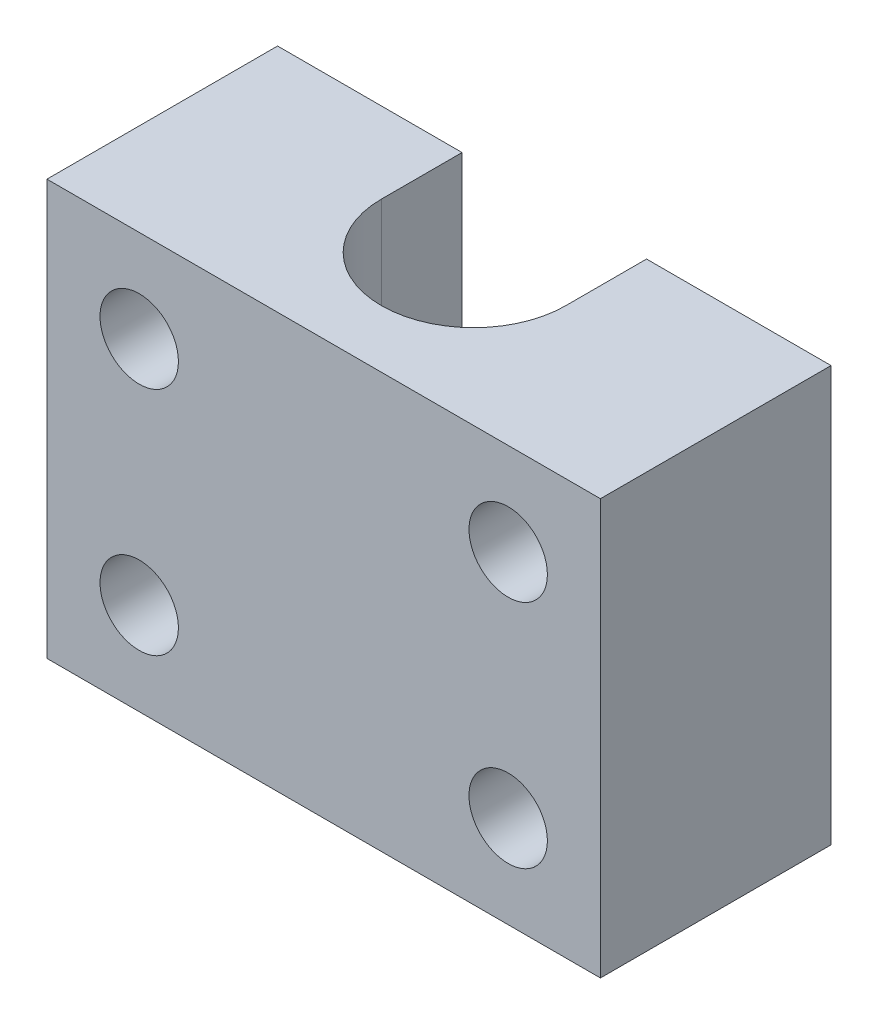
SolidWorks part; units mm, degrees
ref_plane "Front Plane" through (0, 0, 0) normal (0, 0, 1) x (1, 0, 0)
ref_plane "Top Plane" through (0, 0, 0) normal (0, 1, 0) x (1, 0, 0)
ref_plane "Right Plane" through (0, 0, 0) normal (1, 0, 0) x (0, 0, -1)
ref_plane "Plane1" through (0, 0, 6.5) normal (0, 0, 1) x (1, 0, 0)
sketch "Sketch1" plane through (0, 0, 6.5) normal (0, 0, 1) x (1, 0, 0)
  line L0 (12, 9) -> (-12, 9)
  line L1 (-12, 9) -> (-12, -9)
  line L2 (-12, -9) -> (12, -9)
  line L3 (12, -9) -> (12, 9)
extrude "Boss-Extrude1" add sketch "Sketch1" against normal blind 10
sketch "Sketch2" plane through (0, 9, 0) normal (0, 1, 0) x (-1, 0, 0)
  line L0 (-4, -3.5) -> (4, -3.5)
  line L1 (4, -3.5) -> (4, 0)
  line L2 (-4, 0) -> (-4, -3.5)
  arc A0 (4, 0) -> (-4, 0) centre (0, 0) ccw
extrude "Cut-Extrude1" cut sketch "Sketch2" against normal through all
hole_wizard "Hole1" positions "Sketch4" profile "Sketch3" legacy
sketch "Sketch4" plane through (0, 0, 6.5) normal (0, 0, 1) x (1, 0, 0)
  point P0 (8, -5)
sketch "Sketch3" plane through (8, -5, 6.5) normal (1, 0, 0) x (0, -1, 0)
  line L0 (0, 0) -> (0, 10)
  line L1 (0, 10) -> (1.7, 10)
  line L2 (1.7, 10) -> (1.7, 0)
  line L3 (1.7, 0) -> (0, 0)
  line L4 (0, 110) -> (0, -10) construction
  dimension "Diameter" = 3.4
  dimension "Depth" = 10
hole_wizard "Hole2" positions "Sketch6" profile "Sketch5" legacy
sketch "Sketch6" plane through (0, 0, 6.5) normal (0, 0, 1) x (1, 0, 0)
  point P0 (-8, 5)
sketch "Sketch5" plane through (-8, 5, 6.5) normal (1, 0, 0) x (0, -1, 0)
  line L0 (0, 0) -> (0, 10)
  line L1 (0, 10) -> (1.7, 10)
  line L2 (1.7, 10) -> (1.7, 0)
  line L3 (1.7, 0) -> (0, 0)
  line L4 (0, 110) -> (0, -10) construction
  dimension "Diameter" = 3.4
  dimension "Depth" = 10
hole_wizard "Hole3" positions "Sketch8" profile "Sketch7" legacy
sketch "Sketch8" plane through (0, 0, 6.5) normal (0, 0, 1) x (1, 0, 0)
  point P0 (-8, -5)
sketch "Sketch7" plane through (-8, -5, 6.5) normal (1, 0, 0) x (0, -1, 0)
  line L0 (0, 0) -> (0, 10)
  line L1 (0, 10) -> (1.7, 10)
  line L2 (1.7, 10) -> (1.7, 0)
  line L3 (1.7, 0) -> (0, 0)
  line L4 (0, 110) -> (0, -10) construction
  dimension "Diameter" = 3.4
  dimension "Depth" = 10
hole_wizard "Hole4" positions "Sketch10" profile "Sketch9" legacy
sketch "Sketch10" plane through (0, 0, 6.5) normal (0, 0, 1) x (1, 0, 0)
  point P0 (8, 5)
sketch "Sketch9" plane through (8, 5, 6.5) normal (1, 0, 0) x (0, -1, 0)
  line L0 (0, 0) -> (0, 10)
  line L1 (0, 10) -> (1.7, 10)
  line L2 (1.7, 10) -> (1.7, 0)
  line L3 (1.7, 0) -> (0, 0)
  line L4 (0, 110) -> (0, -10) construction
  dimension "Diameter" = 3.4
  dimension "Depth" = 10
